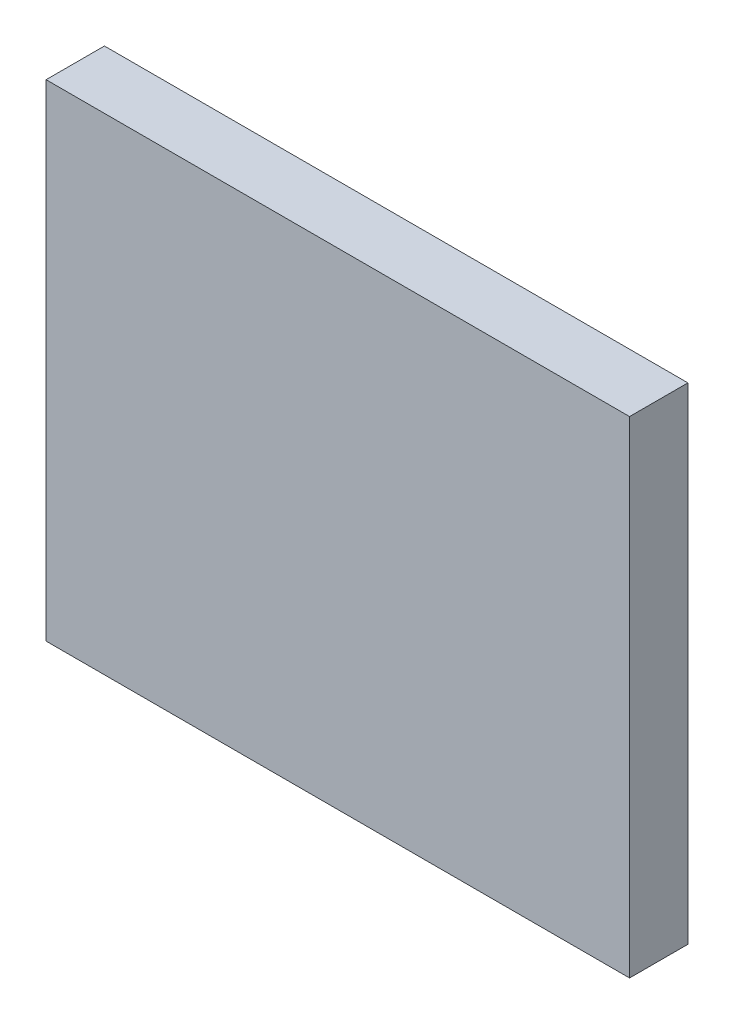
SolidWorks part; units mm, degrees
ref_plane "前视基准面" through (0, 0, 0) normal (0, 0, 1) x (1, 0, 0)
ref_plane "上视基准面" through (0, 0, 0) normal (0, 1, 0) x (1, 0, 0)
ref_plane "右视基准面" through (0, 0, 0) normal (1, 0, 0) x (0, 0, -1)
sketch "草图1" plane through (0, 0, 0) normal (0, 0, 1) x (1, 0, 0)
  line L1 (-15, 12.5) -> (15, 12.5)
  line L2 (-15, 12.5) -> (-15, -12.5)
  line L3 (-15, -12.5) -> (15, -12.5)
  line L4 (15, 12.5) -> (15, -12.5)
  line L5 (-15, 12.5) -> (15, -12.5) construction
  line L6 (-15, -12.5) -> (15, 12.5) construction
  point P0 (0, 0)
  dimension "D1" = 30
  dimension "D2" = 25
extrude "凸台-拉伸1" add sketch "草图1" along normal blind 3
